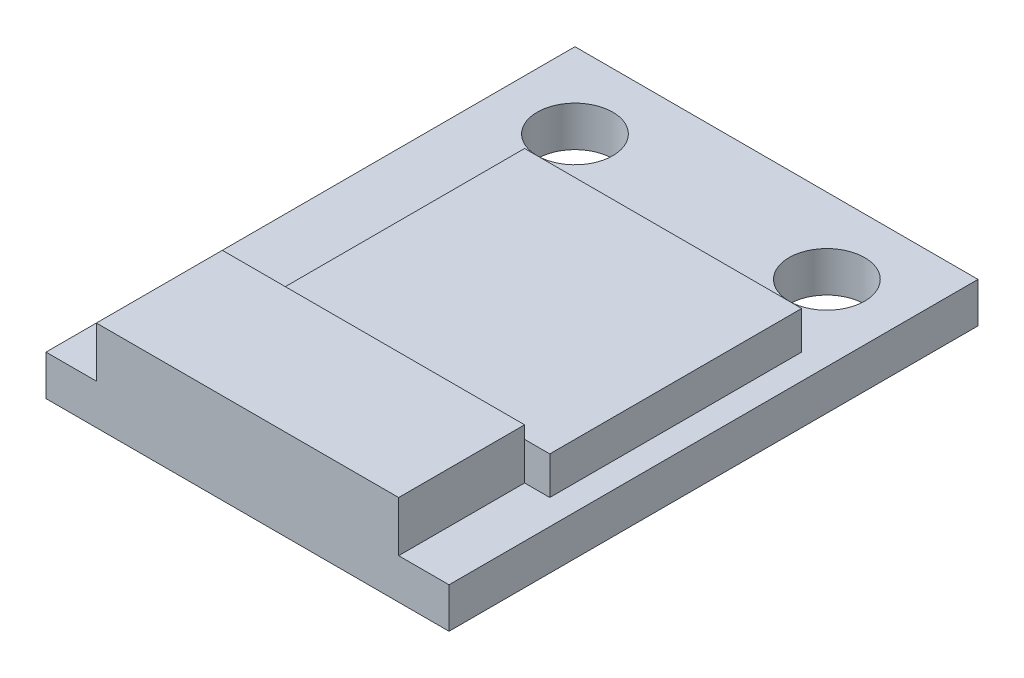
SolidWorks part; units mm, degrees
ref_plane "Front Plane" through (0, 0, 0) normal (0, 0, 1) x (1, 0, 0)
ref_plane "Top Plane" through (0, 0, 0) normal (0, 1, 0) x (1, 0, 0)
ref_plane "Right Plane" through (0, 0, 0) normal (1, 0, 0) x (0, 0, -1)
sketch "Sketch1" plane through (0, 0, 0) normal (0, 1, 0) x (1, 0, 0)
  line L1 (0, 0) -> (16, 0)
  line L2 (0, 0) -> (0, 21)
  line L3 (0, 21) -> (16, 21)
  line L4 (16, 0) -> (16, 21)
  circle A0 centre (3, 18) radius 1.5
  circle A1 centre (13, 18) radius 1.5
  point P9 (0, 0)
  dimension "D3" = 3
  dimension "D1" = 16
  dimension "D2" = 21
  dimension "D4" = 10
  dimension "D5" = 3
  dimension "D6" = 3
extrude "Boss-Extrude1" add sketch "Sketch1" along normal blind 1.6
sketch "Sketch2" plane through (0, 1.6, 0) normal (0, 1, 0) x (1, 0, 0)
  line L0 (16, 0) -> (16, 21) construction
  line L1 (4, 15) -> (15, 15)
  line L2 (4, 15) -> (4, 5)
  line L3 (4, 5) -> (15, 5)
  line L4 (15, 15) -> (15, 5)
  line L5 (0, 0) -> (16, 0) construction
  dimension "D1" = 11
  dimension "D2" = 10
  dimension "D3" = 1
  dimension "D4" = 5
extrude "Boss-Extrude2" add sketch "Sketch2" along normal blind 1.5
sketch "Sketch3" plane through (0, 1.6, 0) normal (0, 1, 0) x (1, 0, 0)
  line L0 (0, 0) -> (16, 0) construction
  line L1 (2, 5) -> (14, 5)
  line L2 (2, 5) -> (2, 0)
  line L3 (2, 0) -> (14, 0)
  line L4 (14, 5) -> (14, 0)
  point P4 (2, 2.5)
  point P5 (8, 0)
  point P8 (8, 0)
  dimension "D1" = 12
  dimension "D2" = 5
extrude "Boss-Extrude3" add sketch "Sketch3" along normal blind 2
